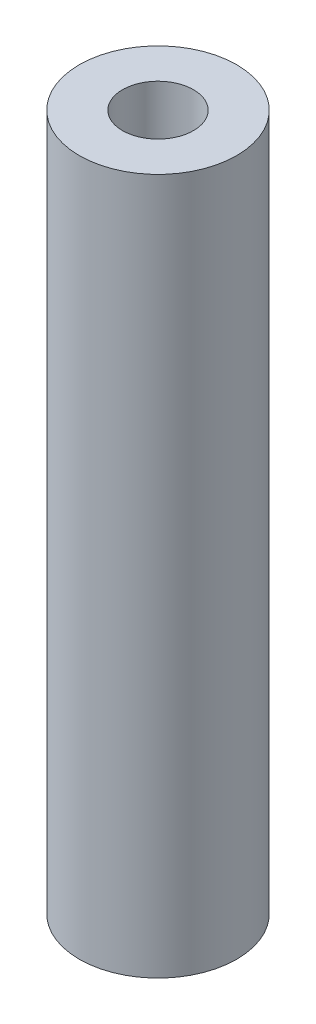
SolidWorks part; units mm, degrees
material "1060 Alloy"
ref_plane "Front Plane" through (0, 0, 0) normal (0, 0, 1) x (1, 0, 0)
ref_plane "Top Plane" through (0, 0, 0) normal (0, 1, 0) x (1, 0, 0)
ref_plane "Right Plane" through (0, 0, 0) normal (1, 0, 0) x (0, 0, -1)
sketch "Sketch1" plane through (0, 0, 0) normal (0, 1, 0) x (1, 0, 0)
  circle A0 centre (0, 0) radius 3
  dimension "D1" = 6
extrude "Boss-Extrude1" add sketch "Sketch1" along normal blind 26.53
hole_wizard "#6-32 Tapped Hole1" positions "Sketch3" profile "Sketch4" tap size "#6-32" standard "ANSI Inch"
sketch "Sketch3" plane through (0, 26.53, 0) normal (0, 1, 0) x (1, 0, 0)
  point P0 (0, 0)
sketch "Sketch4" plane through (0, 26.53, 0) normal (1, 0, 0) x (0, 0, 1)
  line L0 (0, 0) -> (0, 10.8127)
  line L1 (0, 10.8127) -> (1.3525, 10)
  line L2 (1.3525, 10) -> (1.3525, 0)
  line L5 (1.3525, 0) -> (0, 0)
  line L10 (0, 10.8127) -> (-1.3526, 10) construction
  line L11 (0, -6.35) -> (0, 107.95) construction
  dimension "Tap Drill Dia." = 2.7051
  dimension "Tap Drill Depth" = 10
  dimension "Drill Angle" = 118
cosmetic thread "Hole Thread1" parameters "D1"=7.01, "D2"=3.5052
hole_wizard "#6-32 Tapped Hole2" positions "Sketch5" profile "Sketch6" tap size "#6-32" standard "ANSI Inch"
sketch "Sketch5" plane through (0, 0, 0) normal (0, -1, 0) x (-1, 0, 0)
  point P0 (0, 0)
sketch "Sketch6" plane through (0, 0, 0) normal (1, 0, 0) x (0, 0, -1)
  line L0 (0, 0) -> (0, 10.8127)
  line L1 (0, 10.8127) -> (1.3525, 10)
  line L2 (1.3525, 10) -> (1.3525, 0)
  line L5 (1.3525, 0) -> (0, 0)
  line L10 (0, 10.8127) -> (-1.3525, 10) construction
  line L11 (0, -6.35) -> (0, 107.95) construction
  dimension "Tap Drill Dia." = 2.7051
  dimension "Tap Drill Depth" = 10
  dimension "Drill Angle" = 118
cosmetic thread "Hole Thread2" parameters "D1"=7.01, "D2"=3.5052
